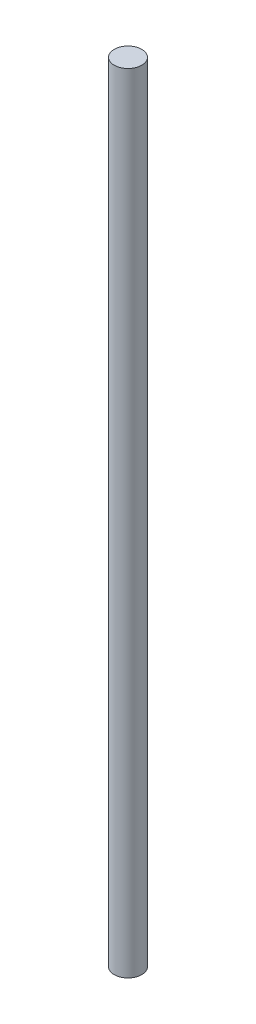
SolidWorks part; units mm, degrees
ref_plane "Front Plane" through (0, 0, 0) normal (0, 0, 1) x (1, 0, 0)
ref_plane "Top Plane" through (0, 0, 0) normal (0, 1, 0) x (1, 0, 0)
ref_plane "Right Plane" through (0, 0, 0) normal (1, 0, 0) x (0, 0, -1)
sketch "Sketch1" plane through (0, 0, 0) normal (0, 1, 0) x (1, 0, 0)
  circle A0 centre (0, 0) radius 0.7
  dimension "D1" = 1.4
extrude "Boss-Extrude1" add sketch "Sketch1" along normal blind 40
